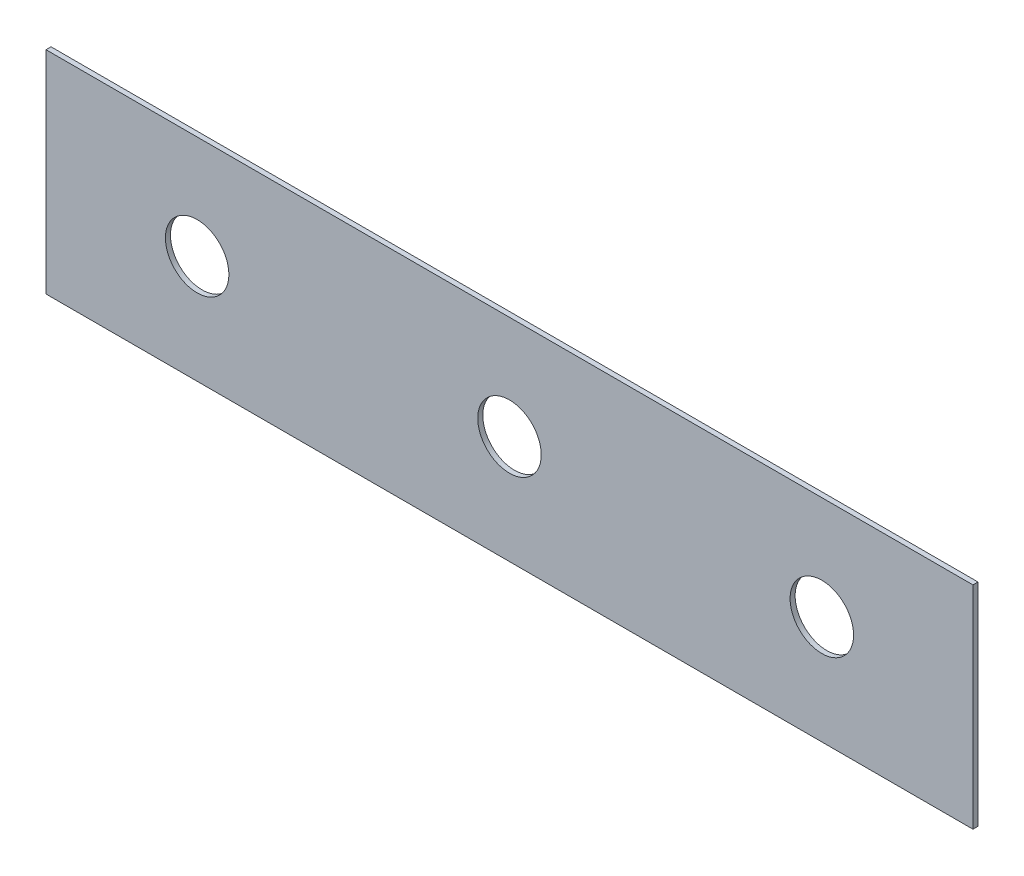
SolidWorks part; units mm, degrees
ref_plane "Front Plane" through (0, 0, 0) normal (0, 0, 1) x (1, 0, 0)
ref_plane "Top Plane" through (0, 0, 0) normal (0, 1, 0) x (1, 0, 0)
ref_plane "Right Plane" through (0, 0, 0) normal (1, 0, 0) x (0, 0, -1)
sketch "Three 12.6 mm locating bores profile" plane through (0, 0, 0) normal (0, 0, 1) x (1, 0, 0)
  line L0 (-92, 7) -> (92, 7)
  line L1 (92, 7) -> (92, 49)
  line L2 (92, 49) -> (-92, 49)
  line L3 (-92, 49) -> (-92, 7)
  circle A0 centre (-62, 28.5) radius 6.3
  circle A1 centre (0, 28.5) radius 6.3
  circle A2 centre (62, 28.5) radius 6.3
extrude "Three 12.6 mm locating bores" add sketch "Three 12.6 mm locating bores profile" along normal blind 1
